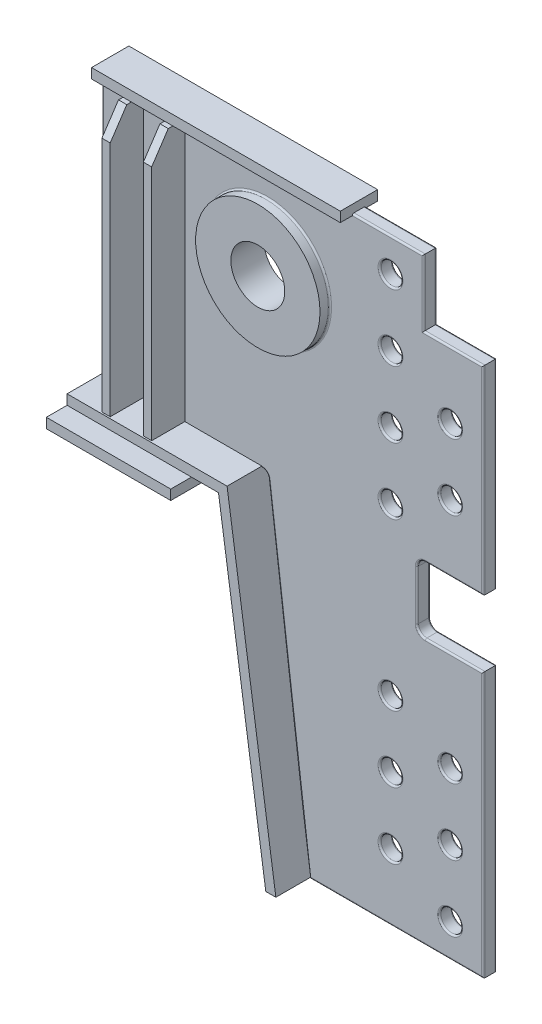
SolidWorks part; units mm, degrees
ref_plane "前视" through (0, 0, 0) normal (0, 0, 1) x (1, 0, 0)
ref_plane "上视" through (0, 0, 0) normal (0, 1, 0) x (1, 0, 0)
ref_plane "右视" through (0, 0, 0) normal (1, 0, 0) x (0, 0, -1)
sketch "草图1" plane through (0, 0, 0) normal (0, 0, 1) x (1, 0, 0)
  line L0 (0, -320) -> (-70, -320)
  line L1 (-72, 0) -> (-460, 0)
  line L2 (-40, 116.6722) -> (-40, -759.2574) construction
  line L3 (0, -720) -> (-210, -720)
  line L4 (-460, 0) -> (-460, -320)
  line L5 (-80, -330) -> (-80, -390)
  line L6 (-70, -400) -> (0, -400)
  line L7 (0, -400) -> (0, -720)
  line L8 (-112, 271.0914) -> (-112, -671.0914) construction
  line L9 (-775.8996, -110) -> (-214.577, -110) construction
  line L15 (-210, -720) -> (-259.124, -327.0077)
  line L16 (-460, -320) -> (-267.0623, -320)
  line L17 (-72, 0) -> (-72, -80)
  line L18 (-72, -80) -> (0, -80)
  line L19 (0, -80) -> (0, -320)
  arc A0 (-80, -330) -> (-70, -320) centre (-70, -330) cw
  arc A1 (-70, -400) -> (-80, -390) centre (-70, -390) cw
  circle A2 centre (-112, -40) radius 13
  circle A3 centre (-112, -120) radius 13
  circle A4 centre (-112, -200) radius 13
  circle A5 centre (-112, -280) radius 13
  circle A6 centre (-40, -160) radius 13
  circle A7 centre (-40, -240) radius 13
  circle A8 centre (-40, -680) radius 13
  circle A9 centre (-40, -600) radius 13
  circle A10 centre (-40, -520) radius 13
  arc A11 (-259.124, -327.0077) -> (-267.0623, -320) centre (-267.0623, -328) ccw
  circle A12 centre (-112, -640) radius 13
  circle A13 centre (-112, -560) radius 13
  circle A14 centre (-112, -480) radius 13
  circle A15 centre (-260, -110) radius 37.5
  point P11 (-80, -320)
  point P49 (-260, -320)
  dimension "D4" = 10
  dimension "D5" = 10
  dimension "D13" = 72
  dimension "D14" = 80
  dimension "D18" = 72
  dimension "D20" = 80
  dimension "D24" = 8
  dimension "D25" = 40
  dimension "D26" = 40
  dimension "D32" = 26
  dimension "D34" = 75
  dimension "D3" = 80
  dimension "D6" = 720
  dimension "D7" = 72
  dimension "D8" = 320
  dimension "D9" = 320
  dimension "D10" = 460
  dimension "D11" = 80
  dimension "D12" = 40
  dimension "D15" = 40
  dimension "D16" = 80
  dimension "D17" = 80
  dimension "D19" = 80
  dimension "D21" = 210
  dimension "D22" = 392.9923
  dimension "D23" = 40
  dimension "D27" = 80
  dimension "D28" = 80
  dimension "D29" = 40
  dimension "D30" = 80
  dimension "D31" = 80
  dimension "D33" = 110
  dimension "D35" = 200
extrude "基体-拉伸" add sketch "草图1" along normal blind 16
sketch "草图2" plane through (0, 0, 16) normal (0, 0, 1) x (1, 0, 0)
  line L0 (-460, 0) -> (-460, -320) construction
  line L1 (-72, 0) -> (-460, 0) construction
  circle A0 centre (-260, -110) radius 32.5
  circle A1 centre (-260, -110) radius 75
  dimension "D1" = 65
  dimension "D4" = 150
  dimension "D2" = 200
  dimension "D3" = 110
extrude "凸台-拉伸1" add sketch "草图2" along normal blind 12 and the other way blind 28
fillet "圆角1" radius 2 28 edges at (-105, -720, 16) (0, -560, 16) (-35, -400, 16) (-77.0711, -397.0711, 16) (-80, -360, 16) (-77.0711, -322.9289, 16) (-35, -320, 16) (0, -200, 16) (-36, -80, 16) (-99, -40, 16) (-72, -40, 16) (-261.7678, -322.0026, 16) (-266, 0, 16) (-99, -120, 16) (-460, -160, 16) (-99, -200, 16) (-363.5311, -320, 16) (-99, -280, 16) (-27, -160, 16) (-27, -240, 16) (-27, -680, 16) (-27, -600, 16) (-27, -520, 16) (-234.562, -523.5039, 16) (-99, -640, 16) (-99, -560, 16) (-99, -480, 16) (-185, -110, 16)
fillet "圆角2" radius 2 28 edges at (-363.5311, -320, 0) (-460, -160, 0) (-266, 0, 0) (-72, -40, 0) (-36, -80, 0) (0, -200, 0) (-35, -320, 0) (-77.0711, -322.9289, 0) (-80, -360, 0) (-77.0711, -397.0711, 0) (-35, -400, 0) (0, -560, 0) (-105, -720, 0) (-234.562, -523.5039, 0) (-261.7678, -322.0026, 0) (-99, -40, 0) (-99, -120, 0) (-99, -200, 0) (-99, -280, 0) (-27, -160, 0) (-27, -240, 0) (-27, -680, 0) (-27, -600, 0) (-27, -520, 0) (-99, -640, 0) (-99, -560, 0) (-99, -480, 0) (-185, -110, 0)
sketch "草图3" plane through (0, 0, 16) normal (0, 0, 1) x (1, 0, 0)
  line L0 (-74, -2) -> (-458, -2) construction
  line L1 (-420, -2) -> (-410, -2)
  line L2 (-420, -2) -> (-420, -318)
  line L3 (-420, -318) -> (-410, -318)
  line L4 (-410, -2) -> (-410, -318)
  line L5 (-458, -318) -> (-267.0623, -318) construction
  line L6 (-460, -320) -> (-460, 0) construction
  line L7 (-370, -2) -> (-360, -2)
  line L8 (-370, -2) -> (-370, -318)
  line L9 (-370, -318) -> (-360, -318)
  line L10 (-360, -2) -> (-360, -318)
  dimension "D1" = 10
  dimension "D2" = 10
  dimension "D3" = 40
  dimension "D4" = 40
extrude "凸台-拉伸2" add sketch "草图3" along normal blind 40 and the other way blind 56
sketch "草图4" plane through (-420, 0, 0) normal (-1, 0, 0) x (0, 0, 1)
  line L0 (-20, -2) -> (-45.5, -32)
  line L1 (0, -2) -> (-40, -2) construction
  line L3 (-20, -2) -> (-45.5, -2)
  line L4 (-45.5, -2) -> (-45.5, -32)
  dimension "D1" = 30
  dimension "D2" = 25.5
extrude "切除-拉伸1" cut sketch "草图4" against normal through all
sketch "草图5" plane through (-420, 0, 0) normal (-1, 0, 0) x (0, 0, 1)
  line L0 (36, -2) -> (56, -32)
  line L1 (56, -2) -> (16, -2) construction
  line L2 (56, -2) -> (56, -318) construction
  line L3 (36, -2) -> (56, -2)
  line L4 (56, -2) -> (56, -32)
  dimension "D1" = 30
extrude "切除-拉伸2" cut sketch "草图5" against normal through all
sketch "草图6" plane through (0, 0, 16) normal (0, 0, 1) x (1, 0, 0)
  line L0 (-460, -320) -> (-460, 0) construction
  line L1 (-267.0623, -318) -> (-460, -318)
  line L2 (-267.0623, -318) -> (-208.2344, -718)
  line L3 (-277.4265, -330) -> (-460, -330)
  line L4 (-460, -318) -> (-460, -330)
  line L6 (-277.4265, -330) -> (-220.3635, -718)
  line L7 (-220.3635, -718) -> (-208.2344, -718)
  dimension "D1" = 12
  dimension "D2" = 12
extrude "凸台-拉伸5" add sketch "草图6" along normal blind 42 and the other way blind 58
sketch "草图7" plane through (0, 0, 0) normal (0, 0, -1) x (-1, 0, 0)
  line L1 (458, -2) -> (158, -2)
  line L2 (458, -2) -> (458, 10)
  line L3 (458, 10) -> (158, 10)
  line L4 (158, -2) -> (158, 10)
  dimension "D1" = 300
  dimension "D2" = 12
extrude "凸台-拉伸6" add sketch "草图7" along normal blind 14.5 and the other way blind 30.5
sketch "草图8" plane through (0, -330, 0) normal (0, -1, 0) x (1, 0, 0)
  line L0 (-515.842, 8) -> (-234.809, 8) construction
  line L1 (-460, -42) -> (-277.4265, -42) construction
  line L2 (-460, 58) -> (-277.4265, 58) construction
  line L4 (-310, 83) -> (-460, 83)
  line L5 (-310, 83) -> (-310, -67)
  line L6 (-310, -67) -> (-460, -67)
  line L7 (-460, 83) -> (-460, -67)
  line L8 (-460, 58) -> (-460, -42) construction
  dimension "D1" = 150
  dimension "D2" = 150
extrude "凸台-拉伸7" add sketch "草图8" along normal blind 12
